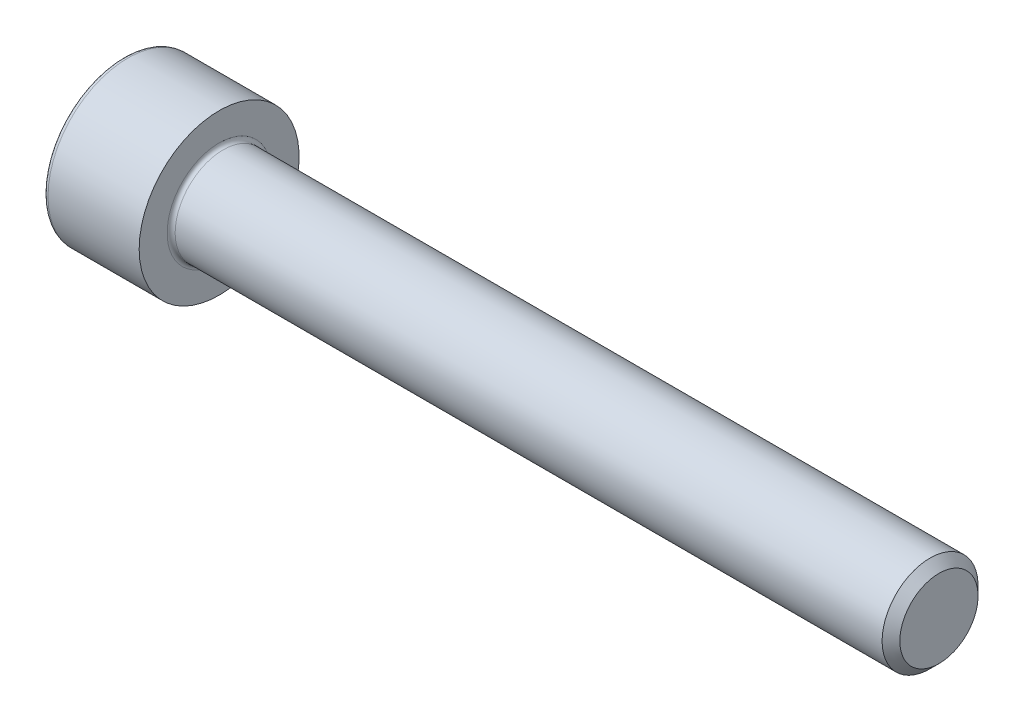
SolidWorks part; units mm, degrees
ref_plane "Plane1" through (0, 0, 0) normal (0, 0, 1) x (1, 0, 0)
ref_plane "Plane2" through (0, 0, 0) normal (0, 1, 0) x (1, 0, 0)
ref_plane "Plane3" through (0, 0, 0) normal (1, 0, 0) x (0, 0, -1)
sketch "BodySke" plane through (0, 0, 0) normal (0, 0, 1) x (1, 0, 0)
  line L0 (0, 0) -> (0, 5)
  line L1 (0, 5) -> (6, 5)
  line L2 (6, 5) -> (6, 3)
  line L3 (6, 3) -> (50.4455, 3)
  line L4 (51, 2.4455) -> (51, 0)
  line L5 (51, 0) -> (0, 0)
  line L6 (-31.75, 0) -> (127, 0) construction
  line L8 (51, 2.4455) -> (50.4455, 3)
  line L10 (51, -2.4455) -> (50.4455, -3) construction
  line L11 (7, 9.525) -> (7, 3.175) construction
  line L12 (27, 9.525) -> (27, 3.175) construction
  line L13 (-9, 9.525) -> (-9, 3.175) construction
  dimension "Diameter" = 6
  dimension "Head_ht" = 6
  dimension "Length" = 45
  dimension "Body_ch_ang" = 45
  dimension "Head_dia" = 10
  dimension "Minor_dia" = 4.891
  dimension "Advance" = 1
  dimension "Thread_nom" = 24
  dimension "Thread_length" = 60
revolve "Base-Revolve" add sketch "BodySke"
cosmetic thread "ThreadCosmetic" [suppressed]
fillet "Fillet1" radius 0.25 1 edges at (6, 0, 3)
fillet "Fillet2" radius 0.3 1 edges at (0, 0, 5)
sketch "Sketch2" plane through (0, 0, 0) normal (0, 0, 1) x (1, 0, 0)
  line L0 (0, 2.542) -> (3, 2.542)
  line L1 (3, 2.542) -> (4.4676, 0)
  line L2 (-31.75, 0) -> (127, 0) construction
  line L3 (4.4676, 0) -> (0, 0)
  line L4 (0, 0) -> (0, 2.542)
  line L6 (0, 0) -> (47.625, 0) construction
  dimension "D1" = 2.542
  dimension "D2" = 60
  dimension "Depth" = 3
revolve "Hex-PreBroach" cut sketch "Sketch2" angle 360 about L6
sketch "Sketch3" plane through (0, 0, 0) normal (-1, 0, 0) x (0, 0.5, 0.866)
  line L0 (1.4676, 2.542) -> (-1.4676, 2.542)
  line L1 (-1.4676, 2.542) -> (-2.9352, 0)
  line L2 (1.4676, 2.542) -> (2.9352, 0)
  line L3 (1.4676, -2.542) -> (2.9352, 0)
  line L4 (1.4676, -2.542) -> (-1.4676, -2.542)
  line L5 (-1.4676, -2.542) -> (-2.9352, 0)
  dimension "D1" = 2.542
  dimension "D2" = 2.542
  dimension "Hex_size" = 5.084
extrude "Hex" cut sketch "Sketch3" against normal blind 3
sketch "ThdSchSke" plane through (0, 0, 0) normal (0, 0, 1) x (1, 0, 0)
  line L0 (27, -2.4455) -> (26.6117, -3)
  line L1 (27, -2.4455) -> (27.3883, -3)
  line L2 (27.3883, -3) -> (27.3883, -3.75)
  line L3 (-3.175, 0) -> (5.1513, 0) construction
  line L4 (0, 4.7) -> (0, -4.7) construction
  line L5 (27.3883, -3.75) -> (26.6117, -3.75)
  line L6 (26.6117, -3.75) -> (26.6117, -3)
  dimension "Thread_minor" = 4.891
  dimension "Diameter" = 6
  dimension "Start" = 27
  dimension "SideAngle" = 55
  dimension "VeeAngle" = 70
  dimension "Overcut" = 7.5
revolve "ThreadSchematic" [suppressed] cut sketch "ThdSchSke" angle 360 about L3
pattern_linear "ThdSchPat" [suppressed]
equation "\"D2@Sketch3\" = \"Hex_size@Sketch3\" / 2"
equation "\"D1@Sketch3\" = \"Hex_size@Sketch3\" / 2"
equation "\"D1@Sketch2\" = \"Hex_size@Sketch3\" / 2"
equation "\"Thread_minor@ThreadCosmetic\"  =  \"Minor_dia@BodySke\""
equation "\"Depth@Sketch2\" =  \"Key_eng@Hex\""
equation "\"Thread_length@ThreadCosmetic\" = ((sgn( (\"Length@BodySke\" - \"Advance@BodySke\" * 3.0) - \"Thread_nom@BodySke\" )-1)*( (\"Length@BodySke\" - \"Advance@BodySke\" * 3.0) - \"Thread_nom@BodySke\" ))/-2+ \"Thread_nom@BodySke\""
equation "\"Thread_minor@ThdSchSke\" = \"Minor_dia@BodySke\""
equation "\"Diameter@ThdSchSke\" = \"Diameter@BodySke\""
equation "\"Overcut@ThdSchSke\" = \"Diameter@BodySke\" * 1.25"
equation "\"Start@ThdSchSke\" = \"Head_ht@BodySke\" + \"Length@BodySke\" - \"Thread_length@ThreadCosmetic\"  '---Non-countersunk---"
equation "\"Num_threads@ThdSchPat\" = int( \"Thread_length@ThreadCosmetic\" / \"Advance@BodySke\" + 0.999 )  + 1"
equation "\"Advance@ThdSchPat\" = \"Thread_length@ThreadCosmetic\" /  (\"Num_threads@ThdSchPat\" - 1) 'relax it"
equation "\"Num_threads@ThdSchPat\" = \"Num_threads@ThdSchPat\" - sgn( \"Num_threads@ThdSchPat\" - 1) '---chamfered tips only---"
